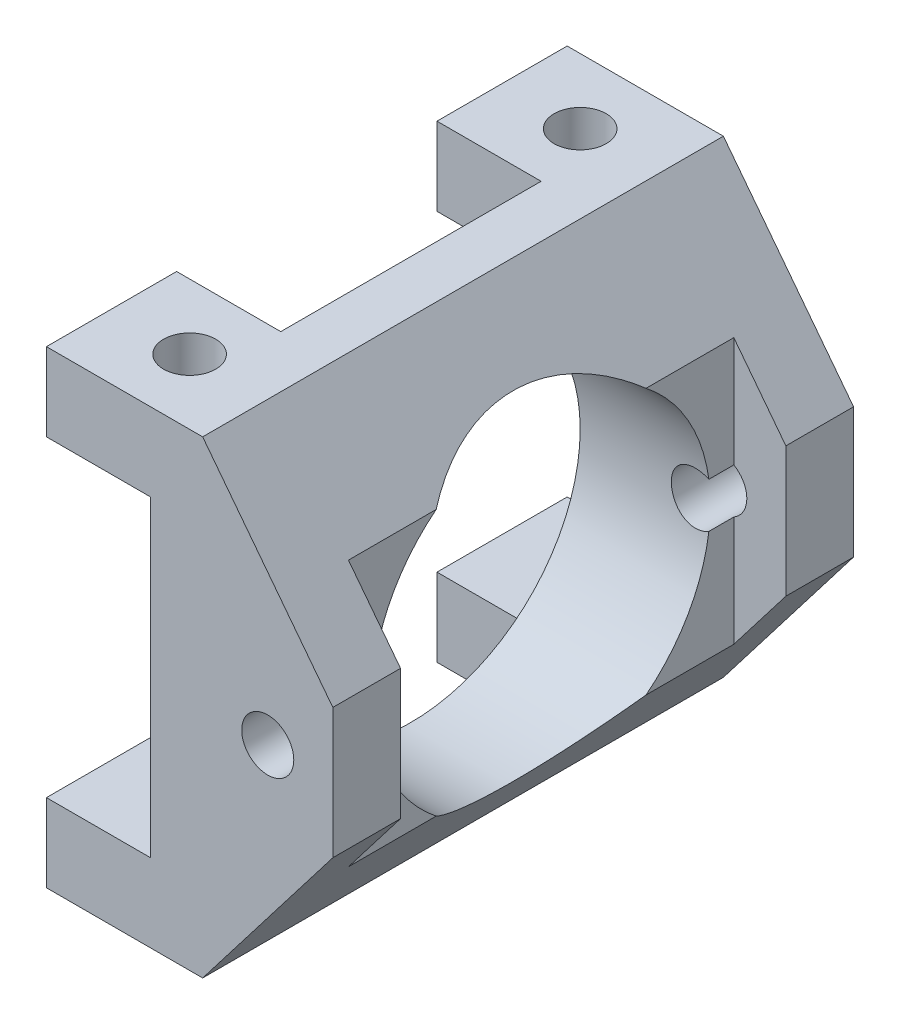
SolidWorks part; units mm, degrees
ref_plane "前视基准面" through (0, 0, 0) normal (0, 0, 1) x (1, 0, 0)
ref_plane "上视基准面" through (0, 0, 0) normal (0, 1, 0) x (1, 0, 0)
ref_plane "右视基准面" through (0, 0, 0) normal (1, 0, 0) x (0, 0, -1)
sketch "草图1" plane through (0, 0, 0) normal (1, 0, 0) x (0, 0, -1)
  line L1 (0, 0) -> (20, 0)
  line L2 (0, 0) -> (0, -18)
  line L3 (0, -18) -> (20, -18)
  line L4 (20, 0) -> (20, -18)
  dimension "D1" = 20
  dimension "D2" = 18
extrude "凸台-拉伸1" add sketch "草图1" along normal blind 5
sketch "草图2" plane through (5, 0, 0) normal (1, 0, 0) x (0, 0, -1)
  line L0 (20, 0) -> (0, 0) construction
  line L1 (0, 0) -> (0, -18) construction
  circle A0 centre (10, -9) radius 6.5
  dimension "D1" = 13
  dimension "D2" = 9
  dimension "D3" = 10
extrude "切除-拉伸1" cut sketch "草图2" against normal through all
sketch "草图3" plane through (5, 0, 0) normal (1, 0, 0) x (0, 0, -1)
  line L0 (0, -18) -> (20, -18) construction
  line L1 (0, 0) -> (2.6, 0)
  line L2 (0, 0) -> (0, -18)
  line L3 (0, -18) -> (2.6, -18)
  line L4 (2.6, 0) -> (2.6, -18)
  line L5 (20, 0) -> (0, 0) construction
  line L6 (20, -18) -> (17.4, -18)
  line L7 (20, -18) -> (20, 0)
  line L8 (20, 0) -> (17.4, 0)
  line L9 (17.4, -18) -> (17.4, 0)
  dimension "D1" = 2.6
  dimension "D2" = 2.6
extrude "凸台-拉伸2" add sketch "草图3" along normal blind 2
sketch "草图4" plane through (0, 0, 0) normal (0, 0, 1) x (1, 0, 0)
  line L0 (7, 0) -> (7, -18) construction
  line L1 (7, -18) -> (0, -18) construction
  circle A0 centre (4.5, -9) radius 1
  point P6 (-12.2368, -0.3311)
  dimension "D1" = 2
  dimension "D2" = 2.5
  dimension "D3" = 9
extrude "切除-拉伸2" cut sketch "草图4" against normal through all
sketch "草图5" plane through (0, 0, 0) normal (0, 0, 1) x (1, 0, 0)
  line L0 (2, 0) -> (7, -6.5)
  line L1 (7, 0) -> (0, 0) construction
  line L2 (7, 0) -> (7, -18) construction
  line L3 (7, -6.5) -> (7, -11.5)
  line L4 (7, -11.5) -> (2, -18)
  line L5 (7, -18) -> (0, -18) construction
  line L6 (2, -18) -> (7, -18)
  line L7 (7, -18) -> (7, -11.5)
  line L8 (2, 0) -> (7, 0)
  line L9 (7, 0) -> (7, -6.5)
  line M7 (0, -18) -> (7, -18)
  line M8 (7, -18) -> (7, 0)
  line M9 (7, 0) -> (0, 0)
  dimension "D1" = 5
  dimension "D2" = 6.5
  dimension "D3" = 6.5
  dimension "D4" = 5
extrude "切除-拉伸3" cut sketch "草图5" against normal through all contours L0 M9 M8 | L4 M8 M7
sketch "草图6" plane through (0, 0, 0) normal (-1, 0, 0) x (0, 0, 1)
  line L1 (-20, -18) -> (-15, -18)
  line L2 (-20, -18) -> (-20, -15)
  line L3 (-20, -15) -> (-15, -15)
  line L4 (-15, -18) -> (-15, -15)
  line L5 (-20, 0) -> (-15, 0)
  line L6 (-20, 0) -> (-20, -3)
  line L7 (-20, -3) -> (-15, -3)
  line L8 (-15, 0) -> (-15, -3)
  line L9 (0, 0) -> (-5, 0)
  line L10 (0, 0) -> (0, -3)
  line L11 (0, -3) -> (-5, -3)
  line L12 (-5, 0) -> (-5, -3)
  line L13 (0, -18) -> (-5, -18)
  line L14 (0, -18) -> (0, -15)
  line L15 (0, -15) -> (-5, -15)
  line L16 (-5, -18) -> (-5, -15)
  dimension "D1" = 3
  dimension "D2" = 3
  dimension "D3" = 3
  dimension "D4" = 3
  dimension "D5" = 5
  dimension "D6" = 5
  dimension "D7" = 5
  dimension "D8" = 5
extrude "凸台-拉伸3" add sketch "草图6" along normal blind 4
sketch "草图7" plane through (0, 0, 0) normal (0, 1, 0) x (1, 0, 0)
  line L0 (-4, 15) -> (-4, 20) construction
  line L1 (2, 20) -> (-4, 20) construction
  line L2 (-4, 0) -> (-4, 5) construction
  line L3 (2, 0) -> (-4, 0) construction
  circle A0 centre (-1, 17.5) radius 1
  circle A1 centre (-1, 2.5) radius 1
  dimension "D1" = 2
  dimension "D2" = 2
  dimension "D3" = 3
  dimension "D4" = 2.5
  dimension "D5" = 3
  dimension "D6" = 2.5
extrude "切除-拉伸4" cut sketch "草图7" against normal through all
